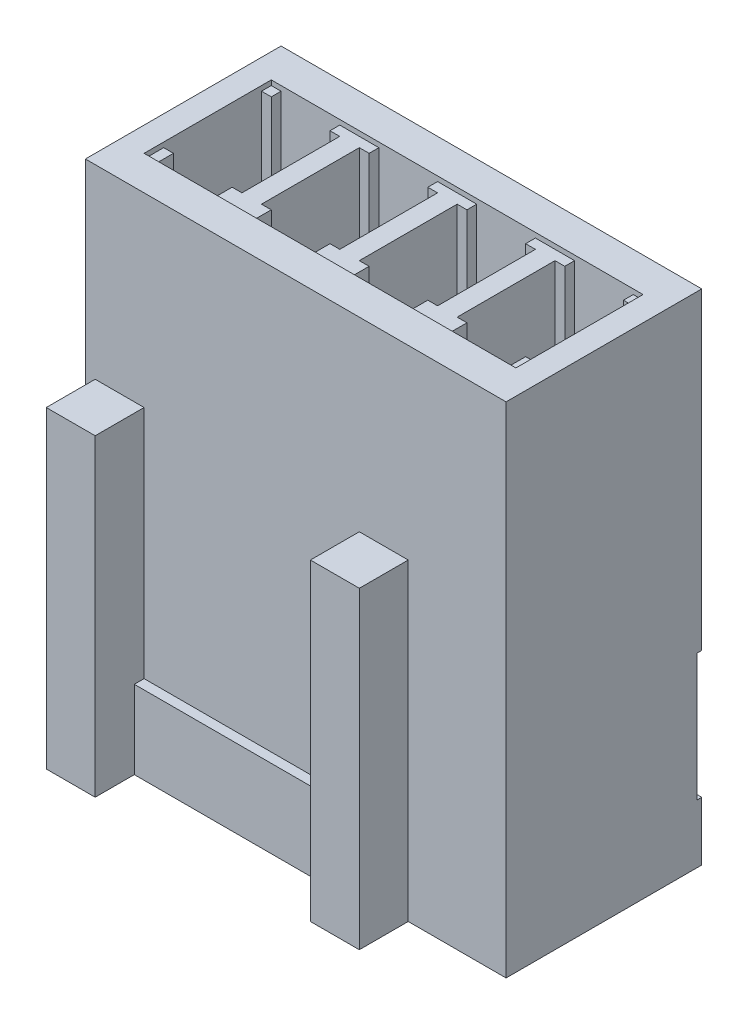
SolidWorks part; units mm, degrees
ref_plane "Ebene vorne" through (0, 0, 0) normal (0, 0, 1) x (1, 0, 0)
ref_plane "Ebene oben" through (0, 0, 0) normal (0, 1, 0) x (1, 0, 0)
ref_plane "Ebene rechts" through (0, 0, 0) normal (1, 0, 0) x (0, 0, -1)
sketch "Skizze1" plane through (0, 0, 0) normal (0, 1, 0) x (1, 0, 0)
  line L1 (-5.375, 2.5) -> (5.375, 2.5)
  line L2 (-5.375, 2.5) -> (-5.375, -2.5)
  line L3 (-5.375, -2.5) -> (5.375, -2.5)
  line L4 (5.375, 2.5) -> (5.375, -2.5)
  line L5 (-5.375, 2.5) -> (5.375, -2.5) construction
  line L6 (-5.375, -2.5) -> (5.375, 2.5) construction
  point P0 (0, 0)
  dimension "D1" = 10.75
  dimension "D2" = 5
extrude "Aufsatz-Linear austragen1" add sketch "Skizze1" along normal blind 12.75
sketch "Skizze2" plane through (0, 0, 0) normal (0, 1, 0) x (1, 0, 0)
  line L0 (-5.375, -2.5) -> (5.375, -2.5) construction
  line L1 (-5.125, -2.5) -> (-3.875, -2.5)
  line L2 (-5.125, -2.5) -> (-5.125, -3.75)
  line L3 (-5.125, -3.75) -> (-3.875, -3.75)
  line L4 (-3.875, -2.5) -> (-3.875, -3.75)
  line L5 (-5.375, 2.5) -> (-5.375, -2.5) construction
  line L6 (1.625, -2.5) -> (2.875, -2.5)
  line L7 (1.625, -2.5) -> (1.625, -3.75)
  line L8 (1.625, -3.75) -> (2.875, -3.75)
  line L9 (2.875, -2.5) -> (2.875, -3.75)
  dimension "D1" = 1.25
  dimension "D2" = 0.25
  dimension "D3" = 5.5
extrude "Aufsatz-Linear austragen2" add sketch "Skizze2" along normal blind 8
sketch "Skizze3" plane through (0, 0, 0) normal (0, 1, 0) x (1, 0, 0)
  line L0 (1.625, -2.5) -> (1.625, -3.75) construction
  line L1 (-3.875, -2.5) -> (1.625, -2.5)
  line L2 (-3.875, -2.5) -> (-3.875, -2.75)
  line L3 (-3.875, -2.75) -> (1.625, -2.75)
  line L4 (1.625, -2.5) -> (1.625, -2.75)
  dimension "D1" = 0.25
extrude "Aufsatz-Linear austragen3" add sketch "Skizze3" along normal blind 2
sketch "Skizze4" plane through (0, 0, 0) normal (0, 1, 0) x (1, 0, 0)
  line L0 (-5.375, 2.5) -> (-5.375, -2.5) construction
  line L1 (-4.5, -1.625) -> (-3, -1.625)
  line L2 (-4.5, -1.625) -> (-4.5, -0.125)
  line L3 (-4.5, -0.125) -> (-3, -0.125)
  line L4 (-3, -1.625) -> (-3, -0.125)
  line L5 (2.875, -2.5) -> (5.375, -2.5) construction
  line L6 (-2, -1.625) -> (-0.5, -1.625)
  line L7 (-2, -1.625) -> (-2, -0.125)
  line L8 (-2, -0.125) -> (-0.5, -0.125)
  line L9 (-0.5, -1.625) -> (-0.5, -0.125)
  line L10 (0.5, -1.625) -> (2, -1.625)
  line L11 (0.5, -1.625) -> (0.5, -0.125)
  line L12 (0.5, -0.125) -> (2, -0.125)
  line L13 (2, -1.625) -> (2, -0.125)
  line L14 (3, -1.625) -> (4.5, -1.625)
  line L15 (3, -1.625) -> (3, -0.125)
  line L16 (3, -0.125) -> (4.5, -0.125)
  line L17 (4.5, -1.625) -> (4.5, -0.125)
  dimension "D1" = 1.5
  dimension "D2" = 0.875
  dimension "D3" = 0.875
  dimension "D4" = 4
extrude "Schnitt-Linear austragen2" cut sketch "Skizze4" along normal through all
chamfer "Fase1" distance 0.25 angle 45 16 edges at (3.75, 0, 1.625) (4.5, 0, 0.875) (3.75, 0, 0.125) (3, 0, 0.875) (2, 0, 0.875) (1.25, 0, 0.125) (0.5, 0, 0.875) (1.25, 0, 1.625) (-1.25, 0, 0.125) (-0.5, 0, 0.875) (-1.25, 0, 1.625) (-2, 0, 0.875) (-3, 0, 0.875) (-3.75, 0, 0.125) (-4.5, 0, 0.875) (-3.75, 0, 1.625)
sketch "Skizze5" plane through (0, 12.75, 0) normal (0, 1, 0) x (1, 0, 0)
  line L0 (-4.5, 1.625) -> (-3, 1.625)
  line L1 (-3, -1.625) -> (-4.5, -1.625) construction
  line L2 (-3, -1.625) -> (-3, 1.625) construction
  line L3 (-3, 1.625) -> (-4.5, 1.625) construction
  line L4 (-4.5, -1.625) -> (-4.5, 1.625) construction
  line L5 (-4.75, -1.125) -> (-2.75, -1.125) construction
  line L6 (-4.75, -1.125) -> (-4.75, 1.375) construction
  line L7 (5.375, 2.5) -> (-5.375, 2.5) construction
  line L8 (-4.75, 1.375) -> (-2.75, 1.375) construction
  line L9 (-2.75, -1.125) -> (-2.75, 1.375) construction
  line L10 (-3, 1.625) -> (-3, 1.375)
  line L11 (-3, 1.375) -> (-2.75, 1.375)
  line L12 (-2.75, 1.375) -> (-2.75, -1.125)
  line L13 (-2.75, -1.125) -> (-3, -1.125)
  line L14 (-3, -1.125) -> (-3, -1.625)
  line L15 (-3, -1.625) -> (-4.5, -1.625)
  line L16 (-4.5, -1.625) -> (-4.5, -1.125)
  line L17 (-4.5, -1.125) -> (-4.75, -1.125)
  line L18 (-4.75, -1.125) -> (-4.75, 1.375)
  line L19 (-4.75, 1.375) -> (-4.5, 1.375)
  line L20 (-4.5, 1.375) -> (-4.5, 1.625)
  line L21 (-2, 1.625) -> (-0.5, 1.625)
  line L22 (-0.5, 1.625) -> (-0.5, 1.375)
  line L23 (-0.5, 1.375) -> (-0.25, 1.375)
  line L24 (-0.25, 1.375) -> (-0.25, -1.125)
  line L25 (-0.25, -1.125) -> (-0.5, -1.125)
  line L26 (-0.5, -1.125) -> (-0.5, -1.625)
  line L27 (-0.5, -1.625) -> (-2, -1.625)
  line L28 (-2, -1.625) -> (-2, -1.125)
  line L29 (-2, -1.125) -> (-2.25, -1.125)
  line L30 (-2.25, -1.125) -> (-2.25, 1.375)
  line L31 (-2.25, 1.375) -> (-2, 1.375)
  line L32 (-2, 1.375) -> (-2, 1.625)
  line L33 (-0.5, -1.625) -> (-2, -1.625) construction
  line L34 (-0.5, -1.625) -> (-0.5, 1.625) construction
  line L35 (-0.5, 1.625) -> (-2, 1.625) construction
  line L36 (-2, -1.625) -> (-2, 1.625) construction
  line L37 (-2.25, -1.125) -> (-0.25, -1.125) construction
  line L38 (-2.25, -1.125) -> (-2.25, 1.375) construction
  line L39 (-2.25, 1.375) -> (-0.25, 1.375) construction
  line L40 (-0.25, -1.125) -> (-0.25, 1.375) construction
  line L41 (0.5, 1.625) -> (2, 1.625)
  line L42 (2, 1.625) -> (2, 1.375)
  line L43 (2, 1.375) -> (2.25, 1.375)
  line L44 (2.25, 1.375) -> (2.25, -1.125)
  line L45 (2.25, -1.125) -> (2, -1.125)
  line L46 (2, -1.125) -> (2, -1.625)
  line L47 (2, -1.625) -> (0.5, -1.625)
  line L48 (0.5, -1.625) -> (0.5, -1.125)
  line L49 (0.5, -1.125) -> (0.25, -1.125)
  line L50 (0.25, -1.125) -> (0.25, 1.375)
  line L51 (0.25, 1.375) -> (0.5, 1.375)
  line L52 (0.5, 1.375) -> (0.5, 1.625)
  line L53 (2, -1.625) -> (0.5, -1.625) construction
  line L54 (2, -1.625) -> (2, 1.625) construction
  line L55 (2, 1.625) -> (0.5, 1.625) construction
  line L56 (0.5, -1.625) -> (0.5, 1.625) construction
  line L57 (0.25, -1.125) -> (2.25, -1.125) construction
  line L58 (0.25, -1.125) -> (0.25, 1.375) construction
  line L59 (0.25, 1.375) -> (2.25, 1.375) construction
  line L60 (2.25, -1.125) -> (2.25, 1.375) construction
  line L61 (3, 1.625) -> (4.5, 1.625)
  line L62 (4.5, 1.625) -> (4.5, 1.375)
  line L63 (4.5, 1.375) -> (4.75, 1.375)
  line L64 (4.75, 1.375) -> (4.75, -1.125)
  line L65 (4.75, -1.125) -> (4.5, -1.125)
  line L66 (4.5, -1.125) -> (4.5, -1.625)
  line L67 (4.5, -1.625) -> (3, -1.625)
  line L68 (3, -1.625) -> (3, -1.125)
  line L69 (3, -1.125) -> (2.75, -1.125)
  line L70 (2.75, -1.125) -> (2.75, 1.375)
  line L71 (2.75, 1.375) -> (3, 1.375)
  line L72 (3, 1.375) -> (3, 1.625)
  line L73 (4.5, -1.625) -> (3, -1.625) construction
  line L74 (4.5, -1.625) -> (4.5, 1.625) construction
  line L75 (4.5, 1.625) -> (3, 1.625) construction
  line L76 (3, -1.625) -> (3, 1.625) construction
  line L77 (2.75, -1.125) -> (4.75, -1.125) construction
  line L78 (2.75, -1.125) -> (2.75, 1.375) construction
  line L79 (2.75, 1.375) -> (4.75, 1.375) construction
  line L80 (4.75, -1.125) -> (4.75, 1.375) construction
  point P12 (-4.5, 1.375)
  point P13 (-3, 1.375)
  point P14 (-3, -1.125)
  point P15 (-4.5, -1.125)
  point P30 (-2, 1.375)
  point P31 (-0.5, 1.375)
  point P32 (-0.5, -1.125)
  point P33 (-2, -1.125)
  point P46 (0.5, 1.375)
  point P47 (2, 1.375)
  point P48 (2, -1.125)
  point P49 (0.5, -1.125)
  point P62 (3, 1.375)
  point P63 (4.5, 1.375)
  point P64 (4.5, -1.125)
  point P65 (3, -1.125)
  dimension "D1" = 0.875
  dimension "D2" = 0.5
  dimension "D3" = 0.25
  dimension "D4" = 0.25
  dimension "D5" = 0.25
  dimension "D6" = 4
extrude "Schnitt-Linear austragen3" cut sketch "Skizze5" against normal blind 12.25
sketch "Skizze6" plane through (0, 12.75, 0) normal (0, 1, 0) x (1, 0, 0)
  line L0 (4.75, -1.125) -> (4.75, 1.375) construction
  line L1 (-4.75, 1.625) -> (4.75, 1.625)
  line L2 (-4.75, 1.625) -> (-4.75, -1.625)
  line L3 (-4.75, -1.625) -> (4.75, -1.625)
  line L4 (4.75, 1.625) -> (4.75, -1.625)
  line L5 (-2, -1.625) -> (-0.5, -1.625) construction
  line L6 (-4.75, 1.375) -> (-4.75, -1.125) construction
  line L7 (-3, 1.625) -> (-4.5, 1.625) construction
extrude "Schnitt-Linear austragen4" cut sketch "Skizze6" against normal blind 0.125
sketch "Skizze7" plane through (0, 0, -2.5) normal (0, 0, -1) x (-1, 0, 0)
  line L0 (-3, 0.5) -> (-3, 12.625) construction
  line L1 (-4.5, 1.5) -> (-3, 1.5)
  line L2 (-4.5, 1.5) -> (-4.5, 4.75)
  line L3 (-4.5, 4.75) -> (-3, 4.75)
  line L4 (-3, 1.5) -> (-3, 4.75)
  line L6 (-2, 1.5) -> (-0.5, 1.5)
  line L7 (-2, 1.5) -> (-2, 4.75)
  line L8 (-2, 4.75) -> (-0.5, 4.75)
  line L9 (-0.5, 1.5) -> (-0.5, 4.75)
  line L11 (-0.5, 0.5) -> (-0.5, 12.625) construction
  line L12 (2, 0.5) -> (2, 12.625) construction
  line L13 (0.5, 1.5) -> (2, 1.5)
  line L14 (0.5, 1.5) -> (0.5, 4.75)
  line L15 (0.5, 4.75) -> (2, 4.75)
  line L16 (2, 1.5) -> (2, 4.75)
  line L17 (4.5, 0.5) -> (4.5, 12.625) construction
  line L18 (3, 1.5) -> (4.5, 1.5)
  line L19 (3, 1.5) -> (3, 4.75)
  line L20 (3, 4.75) -> (4.5, 4.75)
  line L21 (4.5, 1.5) -> (4.5, 4.75)
  line L22 (3, 0.5) -> (3, 12.625) construction
  line L23 (0.5, 0.5) -> (0.5, 12.625) construction
  line L24 (-2, 0.5) -> (-2, 12.625) construction
  line L25 (-4.5, 0.5) -> (-4.5, 12.625) construction
  line L26 (-5.375, 0) -> (5.375, 0) construction
  dimension "D1" = 3.25
  dimension "D2" = 1.5
extrude "Schnitt-Linear austragen5" cut sketch "Skizze7" against normal blind 1
sketch "Skizze8" plane through (0, 0, -2.5) normal (0, 0, -1) x (-1, 0, 0)
  line L0 (-5.375, 12.75) -> (-5.375, 0) construction
  line L1 (-5.375, 4.75) -> (5.375, 4.75)
  line L2 (-5.375, 4.75) -> (-5.375, 1.5)
  line L3 (-5.375, 1.5) -> (5.375, 1.5)
  line L4 (5.375, 4.75) -> (5.375, 1.5)
  line L5 (5.375, 12.75) -> (5.375, 0) construction
  line L6 (-3, 4.75) -> (-4.5, 4.75) construction
  line L8 (-4.5, 1.5) -> (-3, 1.5) construction
extrude "Schnitt-Linear austragen6" cut sketch "Skizze8" against normal blind 0.125
